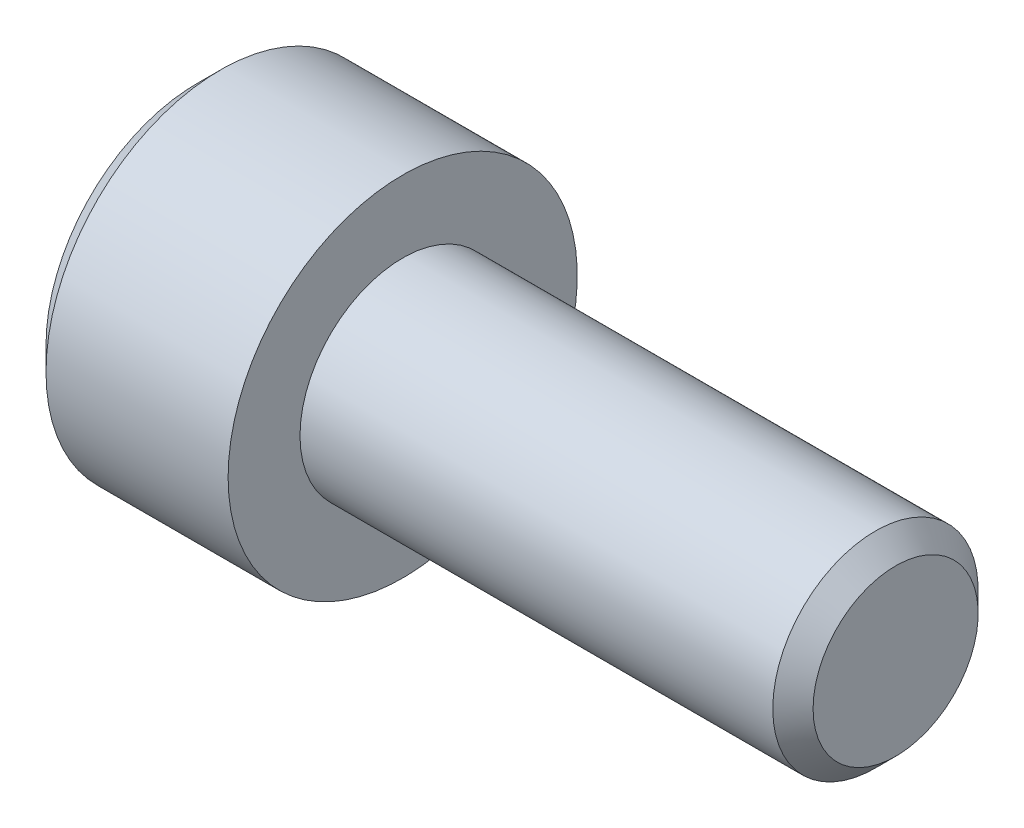
SolidWorks part; units mm, degrees
material "市購件"
ref_plane "前基準面" through (0, 0, 0) normal (0, 0, 1) x (1, 0, 0)
ref_plane "上基準面" through (0, 0, 0) normal (0, 1, 0) x (1, 0, 0)
ref_plane "右基準面" through (0, 0, 0) normal (1, 0, 0) x (0, 0, -1)
sketch "草圖1" plane through (0, 0, 0) normal (0, 0, 1) x (1, 0, 0)
  line L0 (-5, 0) -> (-5, 3.6833)
  line L1 (-5, 3.6833) -> (-4.4333, 4.25)
  line L2 (-4.4333, 4.25) -> (0, 4.25)
  line L3 (0, 4.25) -> (0, 2.5)
  line L4 (0, 2.5) -> (11.5095, 2.5)
  line L5 (11.5095, 2.5) -> (12, 2.0095)
  line L6 (12, 2.0095) -> (12, 0)
  line L7 (12, 0) -> (-5, 0)
  line L8 (12, 0) -> (-5, 0) construction
revolve "旋轉1" add sketch "草圖1" angle 360 about L8
cosmetic thread "裝飾螺紋線1" parameters "D2"=1.202
sketch "草圖2" plane through (0, 0, 0) normal (0, 0, 1) x (1, 0, 0)
  line L0 (-5, 0) -> (-5, 2)
  line L1 (-5, 2) -> (-2.5, 2)
  line L2 (-2.5, 2) -> (-1.9641, 0)
  line L3 (-1.9641, 0) -> (-5, 0)
  line L4 (-1.9641, 0) -> (-5, 0) construction
revolve "除料-旋轉1" cut sketch "草圖2" angle 360 about L4
ref_plane "平面1" through (-5, 0, 0) normal (1, 0, 0) x (0, 0, -1)
sketch "草圖3" plane through (-5, 0, 0) normal (1, 0, 0) x (0, 0, -1)
  line L0 (-2, 1.1547) -> (-2, -1.1547)
  line L1 (-2, -1.1547) -> (0, -2.3094)
  line L2 (0, -2.3094) -> (2, -1.1547)
  line L3 (2, -1.1547) -> (2, 1.1547)
  line L4 (2, 1.1547) -> (0, 2.3094)
  line L5 (0, 2.3094) -> (-2, 1.1547)
extrude "除料-伸長1" cut sketch "草圖3" along normal blind 2.5
